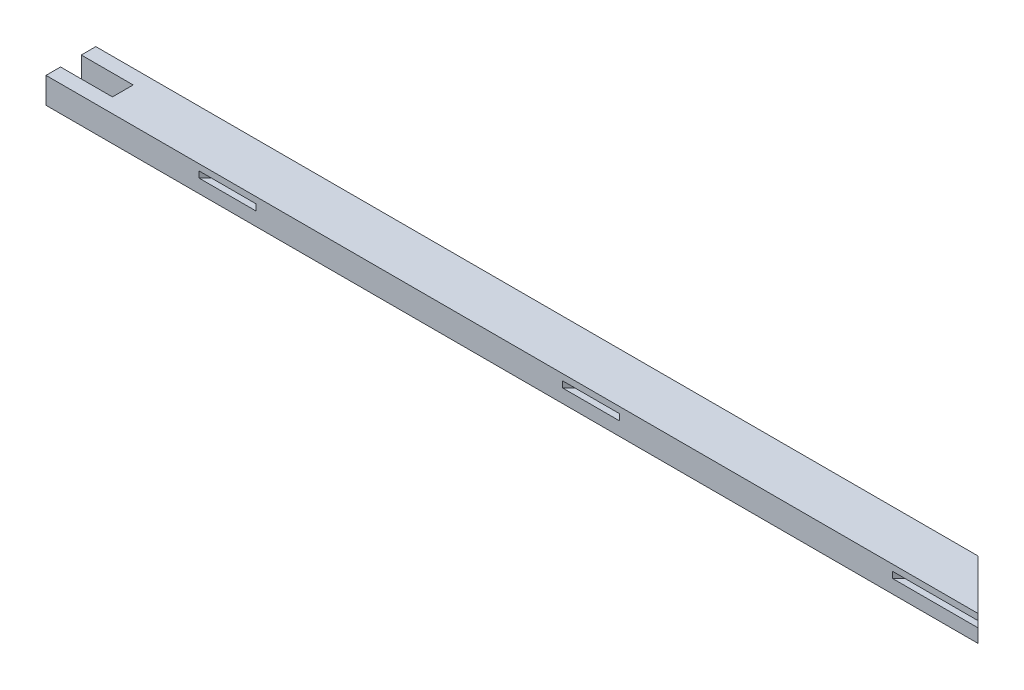
SolidWorks part; units mm, degrees
ref_plane "前视基准面" through (0, 0, 0) normal (0, 0, 1) x (1, 0, 0)
ref_plane "上视基准面" through (0, 0, 0) normal (0, 1, 0) x (1, 0, 0)
ref_plane "右视基准面" through (0, 0, 0) normal (1, 0, 0) x (0, 0, -1)
sketch "草图1" plane through (0, 0, 0) normal (0, 1, 0) x (1, 0, 0)
  line L0 (0, 0) -> (0, -14)
  line L1 (0, -14) -> (50, -14)
  line L2 (50, -14) -> (50, -34)
  line L3 (50, -34) -> (0, -34)
  line L4 (0, -34) -> (0, -48)
  line L5 (0, -48) -> (898, -48)
  line L6 (898, -48) -> (850, 0)
  line L7 (850, 0) -> (0, 0)
  point P8 (913.2428, 0)
  point P10 (856.1979, 0)
  point P11 (50, -24)
  dimension "D1" = 48
  dimension "D2" = 20
  dimension "D3" = 24
  dimension "D4" = 50
  dimension "D5" = 898
  dimension "D6" = 45
extrude "凸台-拉伸1" add sketch "草图1" along normal blind 25
sketch "草图5" plane through (0, 25, 0) normal (0, 1, 0) x (1, 0, 0)
  line L0 (147.5, 0) -> (155, -7.5)
  line L1 (850, 0) -> (0, 0) construction
  line L2 (155, -7.5) -> (195, -7.5)
  line L3 (195, -7.5) -> (202.5, 0)
  line L4 (0, 0) -> (0, -14) construction
  line L5 (147.5, 0) -> (202.5, 0)
  point P8 (175, -7.5)
  dimension "D1" = 40
  dimension "D2" = 90
  dimension "D3" = 135
  dimension "D4" = 7.5
  dimension "D5" = 175
extrude "切除-拉伸2" cut sketch "草图5" against normal blind 6 from offset 6 offset against normal yes
pattern_linear "阵列(线性)1" count 2 spacing 350 along (1, 0, 0) of "切除-拉伸2"
ref_plane "基准面1" through (0, 0, 24) normal (0, 0, 1) x (1, 0, 0)
mirror "镜向1" about plane through (0, 0, 24) normal (0, 0, 1) of "阵列(线性)1", "切除-拉伸2"
sketch "草图6" plane through (0, 25, 0) normal (0, 1, 0) x (1, 0, 0)
  line L0 (890.5, -40.5) -> (823, -40.5)
  line L1 (898, -48) -> (850, 0) construction
  line L2 (823, -40.5) -> (815.5, -48)
  line L3 (0, -48) -> (898, -48) construction
  line L4 (815.5, -48) -> (898, -48)
  line L5 (898, -48) -> (890.5, -40.5)
  dimension "D1" = 75
  dimension "D2" = 7.5
  dimension "D3" = 45
extrude "切除-拉伸3" cut sketch "草图6" against normal blind 6 from offset 6 offset against normal yes
mirror "镜向2" about plane through (0, 0, 24) normal (0, 0, 1) of "切除-拉伸3"
